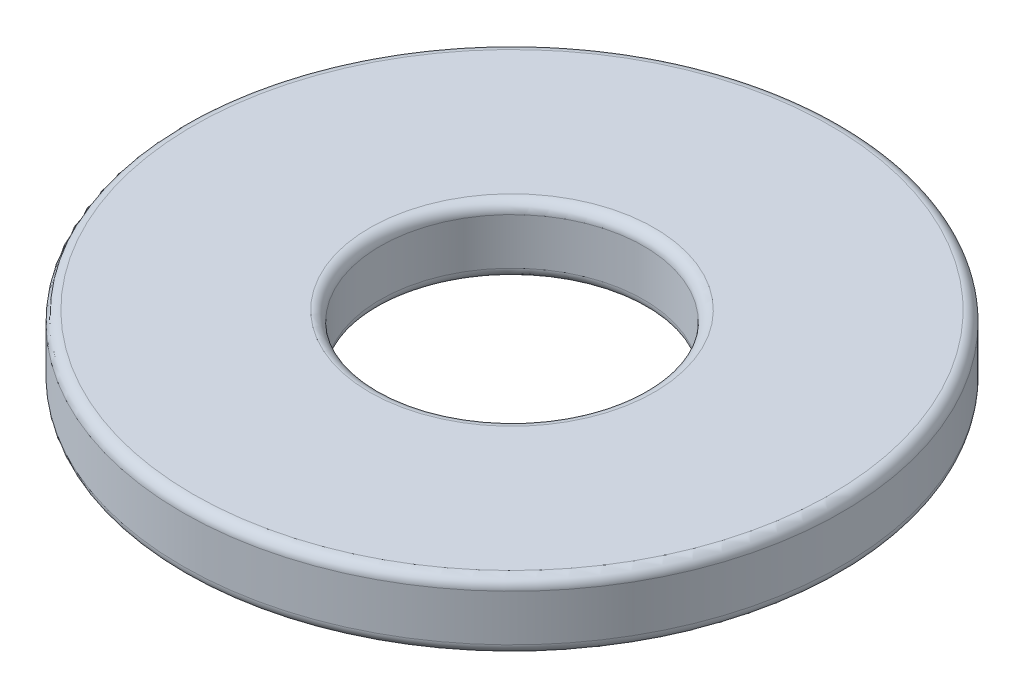
SolidWorks part; units mm, degrees
ref_plane "Front Plane" through (0, 0, 0) normal (0, 0, 1) x (1, 0, 0)
ref_plane "Top Plane" through (0, 0, 0) normal (0, 1, 0) x (1, 0, 0)
ref_plane "Right Plane" through (0, 0, 0) normal (1, 0, 0) x (0, 0, -1)
sketch "Sketch1" plane through (0, 0, 0) normal (0, 1, 0) x (1, 0, 0)
  line L0 (0, 4.0459) -> (0, -5.1128) construction
  line L1 (-7.3861, 0) -> (7.4681, 0) construction
  circle A0 centre (0, 0) radius 1.5875
  circle A1 centre (0, 0) radius 3.9687
  dimension "D1" = 7.9375
  dimension "D2" = 3.175
extrude "Boss-Extrude1" add sketch "Sketch1" along normal blind 0.8128
fillet "Fillet1" radius 0.127 4 edges at (0, 0, 3.9687) (0, 0.8128, 3.9687) (0, 0, 1.5875) (0, 0.8128, 1.5875)
